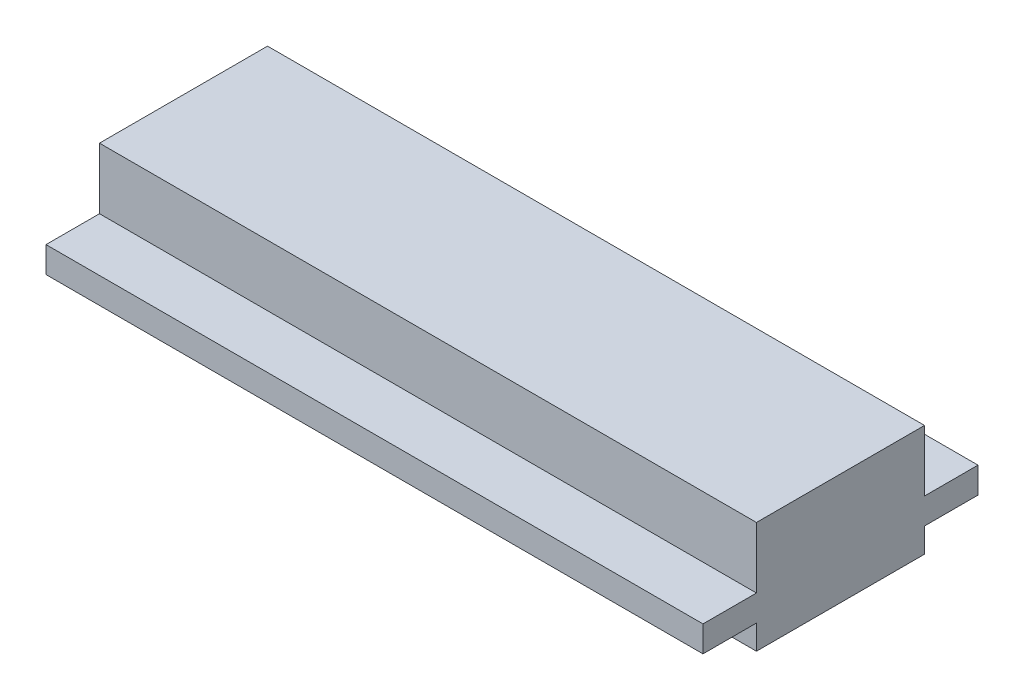
SolidWorks part; units mm, degrees
ref_plane "Front Plane" through (0, 0, 0) normal (0, 0, 1) x (1, 0, 0)
ref_plane "Top Plane" through (0, 0, 0) normal (0, 1, 0) x (1, 0, 0)
ref_plane "Right Plane" through (0, 0, 0) normal (1, 0, 0) x (0, 0, -1)
sketch "Sketch1" plane through (0, 0, 0) normal (0, 1, 0) x (1, 0, 0)
  line L1 (0, 0) -> (43, 0)
  line L2 (0, 0) -> (0, 18)
  line L3 (0, 18) -> (43, 18)
  line L4 (43, 0) -> (43, 18)
  dimension "D1" = 43
  dimension "D2" = 18
extrude "Boss-Extrude1" add sketch "Sketch1" along normal blind 1.7
sketch "Sketch2" plane through (0, 1.7, 0) normal (0, 1, 0) x (1, 0, 0)
  line L0 (0, 9) -> (43, 9) construction
  line L1 (0, 18) -> (0, 0) construction
  line L2 (43, 0) -> (43, 18) construction
  line L4 (43, 3.5) -> (0, 3.5)
  line L5 (43, 3.5) -> (43, 14.5)
  line L6 (43, 14.5) -> (0, 14.5)
  line L7 (0, 3.5) -> (0, 14.5)
  line L8 (43, 3.5) -> (0, 14.5) construction
  line L9 (43, 14.5) -> (0, 3.5) construction
  point P6 (21.5, 9)
  dimension "D1" = 11
extrude "Boss-Extrude2" add sketch "Sketch2" along normal blind 4
sketch "Sketch3" plane through (0, 0, 0) normal (0, -1, 0) x (-1, 0, 0)
  line L0 (0, 9) -> (-43, 9) construction
  line L1 (0, 18) -> (0, 0) construction
  line L2 (-43, 0) -> (-43, 18) construction
  line L4 (-43, 14.5) -> (0, 14.5)
  line L5 (-43, 14.5) -> (-43, 3.5)
  line L6 (-43, 3.5) -> (0, 3.5)
  line L7 (0, 14.5) -> (0, 3.5)
  line L8 (-43, 14.5) -> (0, 3.5) construction
  line L9 (-43, 3.5) -> (0, 14.5) construction
  point P6 (-21.5, 9)
  dimension "D1" = 11
extrude "Boss-Extrude3" add sketch "Sketch3" along normal blind 1.6
